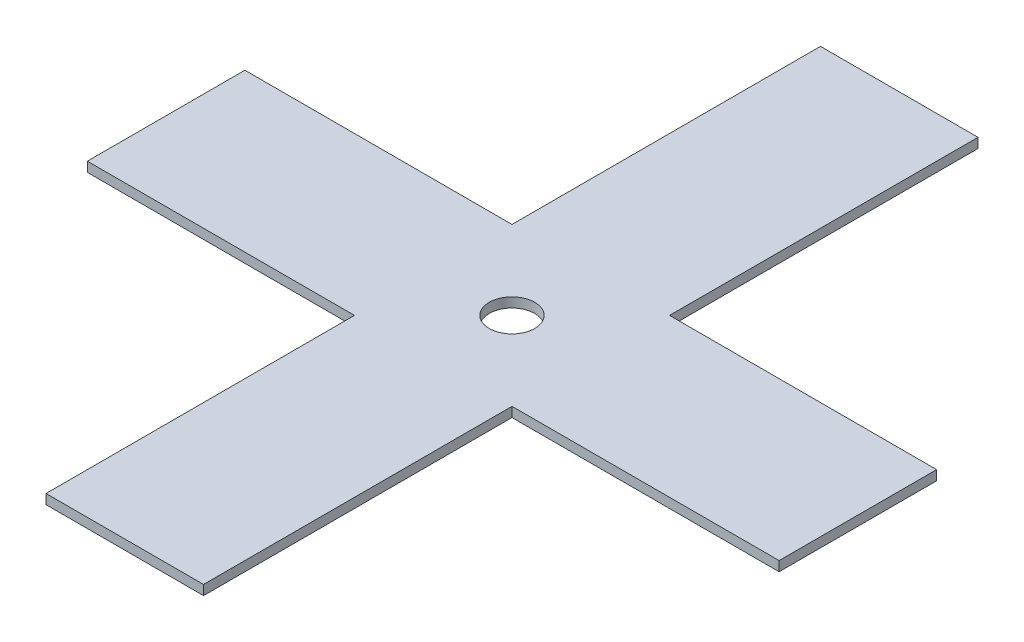
SolidWorks part; units mm, degrees
ref_plane "Front Plane" through (0, 0, 0) normal (0, 0, 1) x (1, 0, 0)
ref_plane "Top Plane" through (0, 0, 0) normal (0, 1, 0) x (1, 0, 0)
ref_plane "Right Plane" through (0, 0, 0) normal (1, 0, 0) x (0, 0, -1)
sketch "Sketch1" plane through (0, 0, 0) normal (0, 1, 0) x (1, 0, 0)
  line L0 (0, 0) -> (0, 37.3)
  line L1 (0, 37.3) -> (-32.3, 37.3)
  line L2 (-32.3, 37.3) -> (-32.3, 56.35)
  line L3 (-32.3, 56.35) -> (0, 56.35)
  line L4 (0, 56.35) -> (0, 93.65)
  line L5 (0, 93.65) -> (19.05, 93.65)
  line L6 (19.05, 93.65) -> (19.05, 56.35)
  line L7 (19.05, 56.35) -> (51.35, 56.35)
  line L8 (51.35, 56.35) -> (51.35, 37.3)
  line L9 (51.35, 37.3) -> (19.05, 37.3)
  line L10 (19.05, 37.3) -> (19.05, 0)
  line L11 (19.05, 0) -> (0, 0)
  line L12 (0, 56.35) -> (19.05, 37.3) construction
  line L13 (0, 37.3) -> (19.05, 56.35) construction
  circle A0 centre (9.525, 46.825) radius 2.75
  dimension "D3" = 5.5
  dimension "D1" = 83.65
  dimension "D2" = 19.05
  dimension "D4" = 93.65
extrude "Boss-Extrude1" add sketch "Sketch1" along normal blind 1.175
